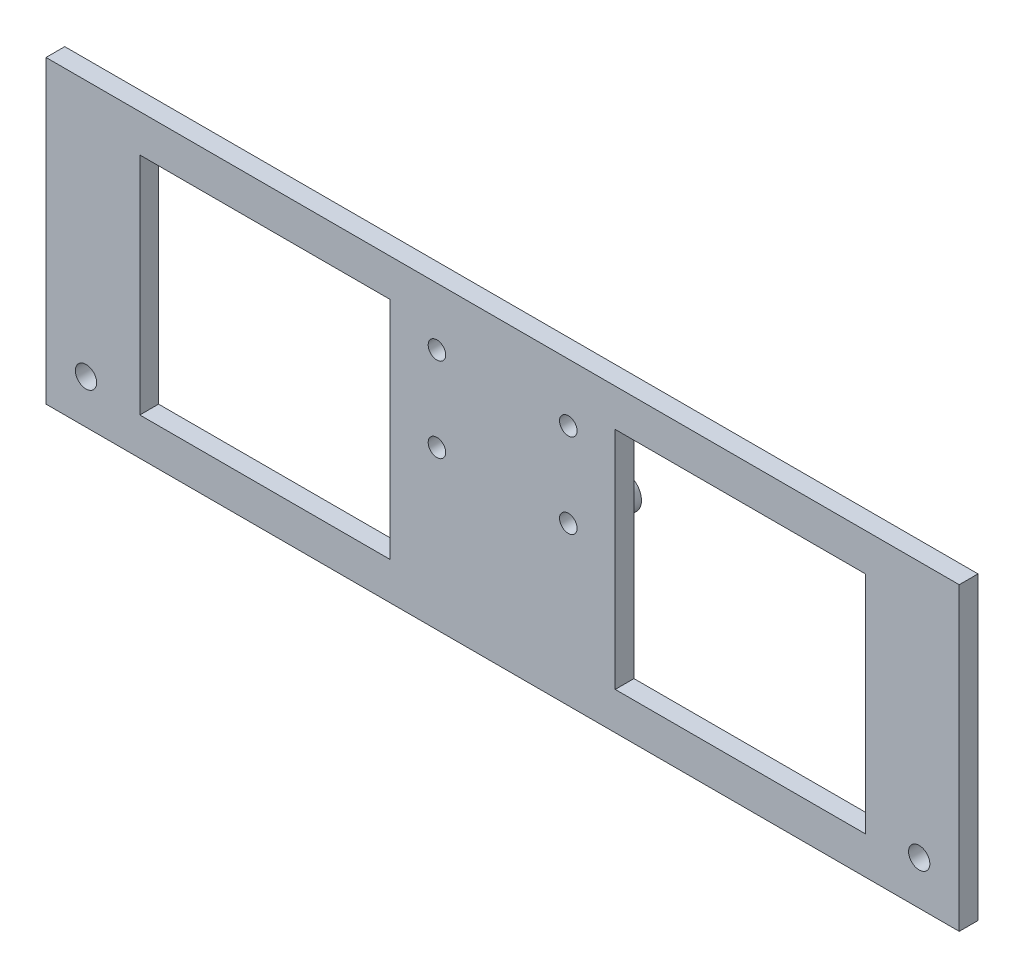
SolidWorks part; units mm, degrees
ref_plane "前视基准面" through (0, 0, 0) normal (0, 0, 1) x (1, 0, 0)
ref_plane "上视基准面" through (0, 0, 0) normal (0, 1, 0) x (1, 0, 0)
ref_plane "右视基准面" through (0, 0, 0) normal (1, 0, 0) x (0, 0, -1)
other "Configuration Table"
sketch "草图1" plane through (0, 0, 0) normal (0, 0, 1) x (1, 0, 0)
  line L1 (-73, -32) -> (73, -32)
  line L2 (-73, -32) -> (-73, 16)
  line L3 (-73, 16) -> (73, 16)
  line L4 (73, -32) -> (73, 16)
  dimension "D1" = 73
  dimension "D2" = 73
  dimension "D3" = 16
  dimension "D4" = 32
extrude "相机横梁146x48" add sketch "草图1" along normal blind 3
sketch "草图2" plane through (0, 0, 0) normal (0, 0, 1) x (1, 0, 0)
  line L1 (-58, -26) -> (-18, -26)
  line L2 (-58, -26) -> (-58, 10)
  line L3 (-58, 10) -> (-18, 10)
  line L4 (-18, -26) -> (-18, 10)
  line L6 (18, -26) -> (58, -26)
  line L7 (18, -26) -> (18, 10)
  line L8 (18, 10) -> (58, 10)
  line L9 (58, -26) -> (58, 10)
  dimension "D1" = 18
  dimension "D2" = 58
  dimension "D3" = 18
  dimension "D4" = 10
  dimension "D5" = 26
extrude "横梁左右减重窗" cut sketch "草图2" against normal through all and the other way through all
sketch "草图3" plane through (0, 0, 0) normal (0, 0, 1) x (1, 0, 0)
  circle A0 centre (-10.5, -6.75) radius 2.7
  circle A1 centre (-10.5, 6.75) radius 2.7
  circle A2 centre (10.5, -6.75) radius 2.7
  circle A3 centre (10.5, 6.75) radius 2.7
  dimension "D1" = 5.4
  dimension "D2" = 10.5
  dimension "D3" = 10.5
  dimension "D4" = 6.75
  dimension "D5" = 6.75
extrude "背面6mm间隔柱" add sketch "草图3" along normal blind 6 from offset 6
sketch "草图4" plane through (0, 0, 0) normal (0, 0, 1) x (1, 0, 0)
  circle A0 centre (-10.5, -6.75) radius 1.4
  circle A1 centre (-10.5, 6.75) radius 1.4
  circle A2 centre (10.5, -6.75) radius 1.4
  circle A3 centre (10.5, 6.75) radius 1.4
  circle A4 centre (-66.6, -25) radius 1.7
  circle A5 centre (66.6, -25) radius 1.7
  dimension "D1" = 3.4
  dimension "D2" = 2.8
  dimension "D3" = 10.5
  dimension "D4" = 66.6
  dimension "D5" = 10.5
  dimension "D6" = 66.6
  dimension "D7" = 6.75
  dimension "D8" = 6.75
  dimension "D9" = 25
extrude "相机2p8孔与梁端3p4孔" cut sketch "草图4" against normal through all and the other way through all
